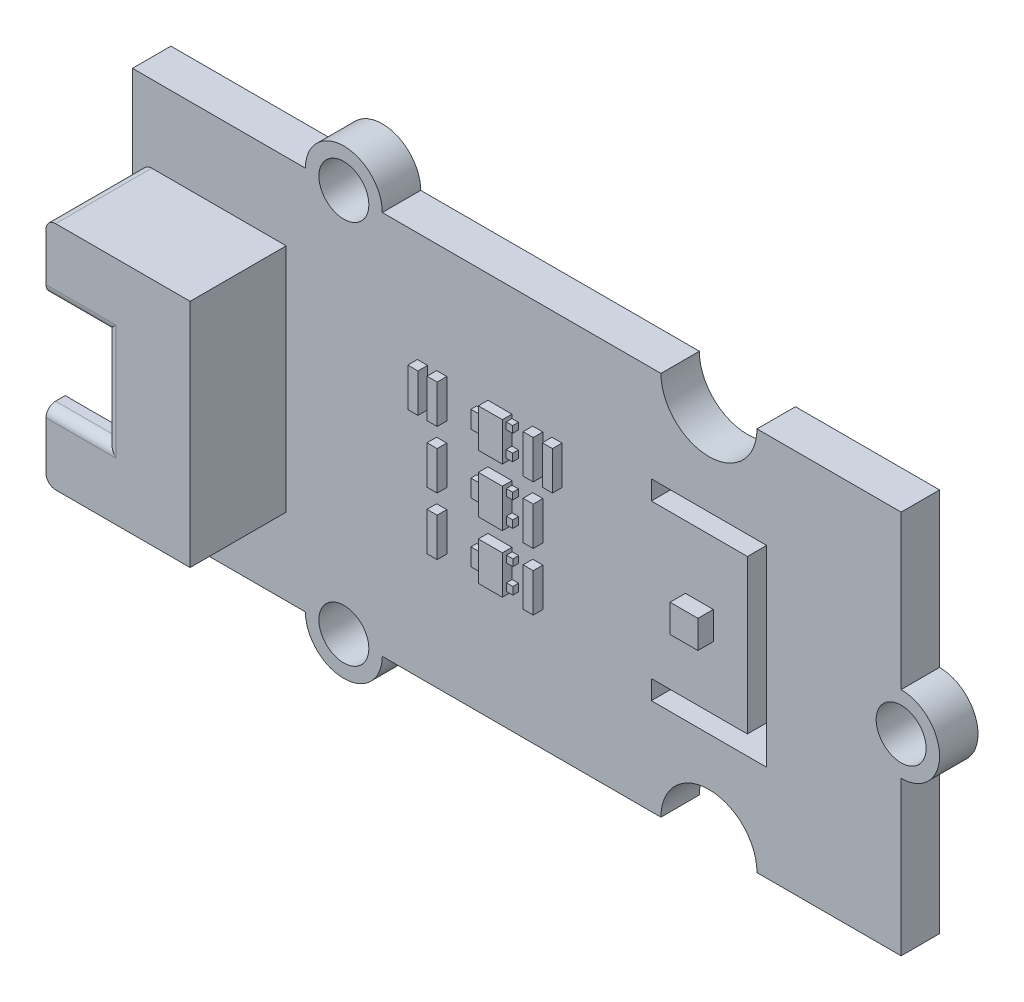
SolidWorks part; units mm, degrees
ref_plane "Front Plane" through (0, 0, 0) normal (0, 0, 1) x (1, 0, 0)
ref_plane "Top Plane" through (0, 0, 0) normal (0, 1, 0) x (1, 0, 0)
ref_plane "Right Plane" through (0, 0, 0) normal (1, 0, 0) x (0, 0, -1)
sketch "Sketch1" plane through (0, 0, 0) normal (0, 0, 1) x (1, 0, 0)
  line L0 (0, 0) -> (9, 0)
  line L1 (40, 0) -> (40, 8)
  line L2 (0, 20) -> (9, 20)
  line L3 (0, 20) -> (0, 0)
  line L4 (40, 20) -> (40, 12)
  line L5 (32.5, 20) -> (40, 20)
  line L6 (32.5, 0) -> (40, 0)
  line L8 (13, 20) -> (27.5, 20)
  line L10 (13, 0) -> (27.5, 0)
  line L12 (33, 15) -> (27, 15)
  line L13 (27, 15) -> (27, 14)
  line L14 (27, 6) -> (32, 6)
  line L15 (27, 14) -> (32, 14)
  line L16 (32, 14) -> (32, 6)
  line L17 (33, 15) -> (33, 5)
  line L19 (27, 5) -> (27, 6)
  line L20 (33, 5) -> (27, 5)
  arc A0 (13, 20) -> (9, 20) centre (11, 20) ccw
  circle A1 centre (11, 20) radius 1.3
  circle A2 centre (11, 0) radius 1.3
  arc A3 (13, 0) -> (9, 0) centre (11, 0) cw
  arc A4 (40, 8) -> (40, 12) centre (40, 10) ccw
  circle A5 centre (40, 10) radius 1.3
  arc A6 (27.5, 20) -> (32.5, 20) centre (30, 20) ccw
  arc A7 (27.5, 0) -> (32.5, 0) centre (30, 0) cw
  point P35 (32, 10)
extrude "Boss-Extrude1" add sketch "Sketch1" along normal blind 2
sketch "Sketch2" plane through (0, 0, 2) normal (0, 0, 1) x (1, 0, 0)
  line L1 (0, 20) -> (0, 0) construction
  line L2 (0, 10) -> (0, 16)
  line L3 (0, 16) -> (8, 16)
  line L4 (8, 16) -> (8, 4)
  line L5 (8, 4) -> (0, 4)
  line L6 (0, 4) -> (0, 10)
extrude "Boss-Extrude2" add sketch "Sketch2" along normal blind 5
sketch "Sketch3" plane through (0, 0, 0) normal (-1, 0, 0) x (0, 0, 1)
  line L0 (6, 5) -> (2, 5)
  line L4 (2, 15) -> (2, 5)
  line L5 (6, 15) -> (6, 5)
  line L6 (6, 15) -> (2, 15)
extrude "Cut-Extrude1" cut sketch "Sketch3" against normal blind 7
sketch "Sketch4" plane through (0, 0, 0) normal (-1, 0, 0) x (0, 0, 1)
  line L1 (7, 16) -> (2, 16)
  line L2 (7, 16) -> (7, 4)
  line L3 (7, 4) -> (2, 4)
  line L4 (2, 16) -> (2, 4)
extrude "Cut-Extrude2" cut sketch "Sketch4" against normal blind 0.5
sketch "Sketch5" plane through (0, 0, 7) normal (0, 0, 1) x (1, 0, 0)
  line L0 (0.5, 12.5) -> (0.5, 7.5)
  line L1 (0.5, 4) -> (0.5, 16) construction
  line L2 (3.6388, 7.5) -> (3.6388, 12.5)
  line L3 (3.6388, 12.5) -> (0.5, 12.5)
  line L5 (0.5, 10) -> (0.4947, 9.8975)
  line L6 (3.6388, 7.5) -> (0.5, 7.5)
  line L7 (0.5, 10) -> (0.4947, 10.1025)
  line M4 (0.5, 16) -> (0.5, 4)
extrude "Cut-Extrude3" cut sketch "Sketch5" against normal blind 1.5 contours L6 L2 L3 L0 M4
fillet "Fillet1" radius 0.5 5 edges at (0.5, 4, 4.5) (0.5, 16, 4.5) (2.0694, 7.5, 7) (3.6388, 10, 7) (2.0694, 12.5, 7)
sketch "Sketch6" plane through (0, 0, 2) normal (0, 0, 1) x (1, 0, 0)
  line L3 (28.7746, 10.7254) -> (30.2254, 10.7254)
  line L4 (28.7746, 10.7254) -> (28.7746, 9.2746)
  line L5 (28.7746, 9.2746) -> (30.2254, 9.2746)
  line L6 (30.2254, 10.7254) -> (30.2254, 9.2746)
extrude "Boss-Extrude3" add sketch "Sketch6" along normal blind 0.8
sketch "Sketch7" plane through (0, 0, 2) normal (0, 0, 1) x (1, 0, 0)
  line L0 (15.8276, 14.2891) -> (15.8276, 12.2854)
  line L1 (14.8276, 14.2891) -> (15.3557, 14.2891)
  line L2 (14.8276, 14.2891) -> (14.8276, 12.2854)
  line L3 (14.8276, 12.2854) -> (15.3557, 12.2854)
  line L4 (15.3557, 14.2891) -> (15.3557, 12.2854)
  line L5 (15.8276, 14.2891) -> (16.3557, 14.2891)
  line L6 (16.3557, 14.2891) -> (16.3557, 12.2854)
  line L7 (15.8276, 12.2854) -> (16.3557, 12.2854)
  line L8 (15.8276, 11.2891) -> (15.8276, 9.2854)
  line L9 (15.8276, 11.2891) -> (16.3557, 11.2891)
  line L10 (16.3557, 11.2891) -> (16.3557, 9.2854)
  line L11 (15.8276, 9.2854) -> (16.3557, 9.2854)
  line L12 (15.8276, 8.2891) -> (15.8276, 6.2854)
  line L13 (15.8276, 8.2891) -> (16.3557, 8.2891)
  line L14 (16.3557, 8.2891) -> (16.3557, 6.2854)
  line L15 (15.8276, 6.2854) -> (16.3557, 6.2854)
  line L24 (21.8276, 14.2891) -> (21.8276, 12.2854)
  line L25 (20.8276, 14.2891) -> (21.3557, 14.2891)
  line L26 (20.8276, 14.2891) -> (20.8276, 12.2854)
  line L27 (20.8276, 12.2854) -> (21.3557, 12.2854)
  line L28 (21.3557, 14.2891) -> (21.3557, 12.2854)
  line L29 (21.8276, 14.2891) -> (22.3557, 14.2891)
  line L30 (22.3557, 14.2891) -> (22.3557, 12.2854)
  line L31 (21.8276, 12.2854) -> (22.3557, 12.2854)
  line L40 (20.8276, 11.2891) -> (20.8276, 9.2854)
  line L41 (20.8276, 11.2891) -> (21.3557, 11.2891)
  line L42 (21.3557, 11.2891) -> (21.3557, 9.2854)
  line L43 (20.8276, 9.2854) -> (21.3557, 9.2854)
  line L44 (20.8276, 8.2891) -> (20.8276, 6.2854)
  line L45 (20.8276, 8.2891) -> (21.3557, 8.2891)
  line L46 (21.3557, 8.2891) -> (21.3557, 6.2854)
  line L47 (20.8276, 6.2854) -> (21.3557, 6.2854)
  line L48 (21.8276, 11.2891) -> (21.8276, 9.2854) [skipped]
  line L49 (21.8276, 11.2891) -> (22.3557, 11.2891) [skipped]
  line L50 (22.3557, 11.2891) -> (22.3557, 9.2854) [skipped]
  line L51 (21.8276, 9.2854) -> (22.3557, 9.2854) [skipped]
  line L52 (21.8276, 8.2891) -> (21.8276, 6.2854) [skipped]
  line L53 (21.8276, 8.2891) -> (22.3557, 8.2891) [skipped]
  line L54 (22.3557, 8.2891) -> (22.3557, 6.2854) [skipped]
  line L55 (21.8276, 6.2854) -> (22.3557, 6.2854) [skipped]
  line L56 (14.8276, 11.2891) -> (14.8276, 9.2854) [skipped]
  line L57 (14.8276, 11.2891) -> (15.3557, 11.2891) [skipped]
  line L58 (15.3557, 11.2891) -> (15.3557, 9.2854) [skipped]
  line L59 (14.8276, 9.2854) -> (15.3557, 9.2854) [skipped]
  line L60 (14.8276, 8.2891) -> (14.8276, 6.2854) [skipped]
  line L61 (14.8276, 8.2891) -> (15.3557, 8.2891) [skipped]
  line L62 (15.3557, 8.2891) -> (15.3557, 6.2854) [skipped]
  line L63 (14.8276, 6.2854) -> (15.3557, 6.2854) [skipped]
  dimension "D1" = 2
  dimension "D2" = 3
  dimension "D3" = 2
extrude "Boss-Extrude4" add sketch "Sketch7" along normal blind 0.5
sketch "Sketch8" plane through (0, 0, 2) normal (0, 0, 1) x (1, 0, 0)
  line L0 (18.4972, 11.2891) -> (18.4972, 9.2854)
  line L1 (18.4972, 14.2891) -> (19.7478, 14.2891)
  line L2 (18.4972, 14.2891) -> (18.4972, 12.2854)
  line L3 (18.4972, 12.2854) -> (19.7478, 12.2854)
  line L4 (19.7478, 14.2891) -> (19.7478, 12.2854)
  line L5 (18.4972, 11.2891) -> (19.7478, 11.2891)
  line L6 (19.7478, 11.2891) -> (19.7478, 9.2854)
  line L7 (18.4972, 9.2854) -> (19.7478, 9.2854)
  line L8 (18.4972, 8.2891) -> (18.4972, 6.2854)
  line L9 (18.4972, 8.2891) -> (19.7478, 8.2891)
  line L10 (19.7478, 8.2891) -> (19.7478, 6.2854)
  line L11 (18.4972, 6.2854) -> (19.7478, 6.2854)
  dimension "D1" = 3
extrude "Boss-Extrude5" add sketch "Sketch8" along normal blind 0.5
sketch "Sketch9" plane through (0, 0, 2) normal (0, 0, 1) x (1, 0, 0)
  line L0 (18.4972, 14.2891) -> (18.4972, 12.2854) construction
  line L1 (18.4972, 13.7394) -> (17.9102, 13.7394)
  line L2 (18.4972, 13.7394) -> (18.4972, 12.8454)
  line L3 (18.4972, 12.8454) -> (17.9102, 12.8454)
  line L4 (17.9102, 13.7394) -> (17.9102, 12.8454)
  line L5 (18.4972, 10.6394) -> (18.4972, 9.7454)
  line L6 (18.4972, 10.6394) -> (17.9102, 10.6394)
  line L7 (17.9102, 10.6394) -> (17.9102, 9.7454)
  line L8 (18.4972, 9.7454) -> (17.9102, 9.7454)
  line L9 (18.4972, 7.5394) -> (18.4972, 6.6454)
  line L10 (18.4972, 7.5394) -> (17.9102, 7.5394)
  line L11 (17.9102, 7.5394) -> (17.9102, 6.6454)
  line L12 (18.4972, 6.6454) -> (17.9102, 6.6454)
  line L13 (19.7478, 12.2854) -> (19.7478, 14.2891) construction
  line L14 (19.7478, 14.0901) -> (20.0815, 14.0901)
  line L15 (19.7478, 14.0901) -> (19.7478, 13.7394)
  line L16 (19.7478, 13.7394) -> (20.0815, 13.7394)
  line L17 (20.0815, 14.0901) -> (20.0815, 13.7394)
  line L18 (19.7548, 9.8454) -> (19.7548, 9.4554)
  line L19 (19.7478, 12.8454) -> (20.0815, 12.8454)
  line L20 (19.7478, 12.8454) -> (19.7478, 12.4554)
  line L21 (19.7478, 12.4554) -> (20.0815, 12.4554)
  line L22 (20.0815, 12.8454) -> (20.0815, 12.4554)
  line L23 (19.7548, 9.8454) -> (20.0885, 9.8454)
  line L24 (20.0885, 9.8454) -> (20.0885, 9.4554)
  line L25 (19.7548, 9.4554) -> (20.0885, 9.4554)
  line L26 (19.7548, 10.7394) -> (20.0885, 10.7394)
  line L27 (20.0885, 11.0901) -> (20.0885, 10.7394)
  line L28 (19.7548, 11.0901) -> (20.0885, 11.0901)
  line L29 (19.7548, 11.0901) -> (19.7548, 10.7394)
  line L30 (19.7618, 6.8454) -> (19.7618, 6.4554)
  line L31 (19.7618, 6.8454) -> (20.0955, 6.8454)
  line L32 (20.0955, 6.8454) -> (20.0955, 6.4554)
  line L33 (19.7618, 6.4554) -> (20.0955, 6.4554)
  line L34 (19.7618, 7.7394) -> (20.0955, 7.7394)
  line L35 (20.0955, 8.0901) -> (20.0955, 7.7394)
  line L36 (19.7618, 8.0901) -> (20.0955, 8.0901)
  line L37 (19.7618, 8.0901) -> (19.7618, 7.7394)
  dimension "D1" = 3
  dimension "D2" = 3
extrude "Boss-Extrude6" add sketch "Sketch9" along normal blind 0.3
